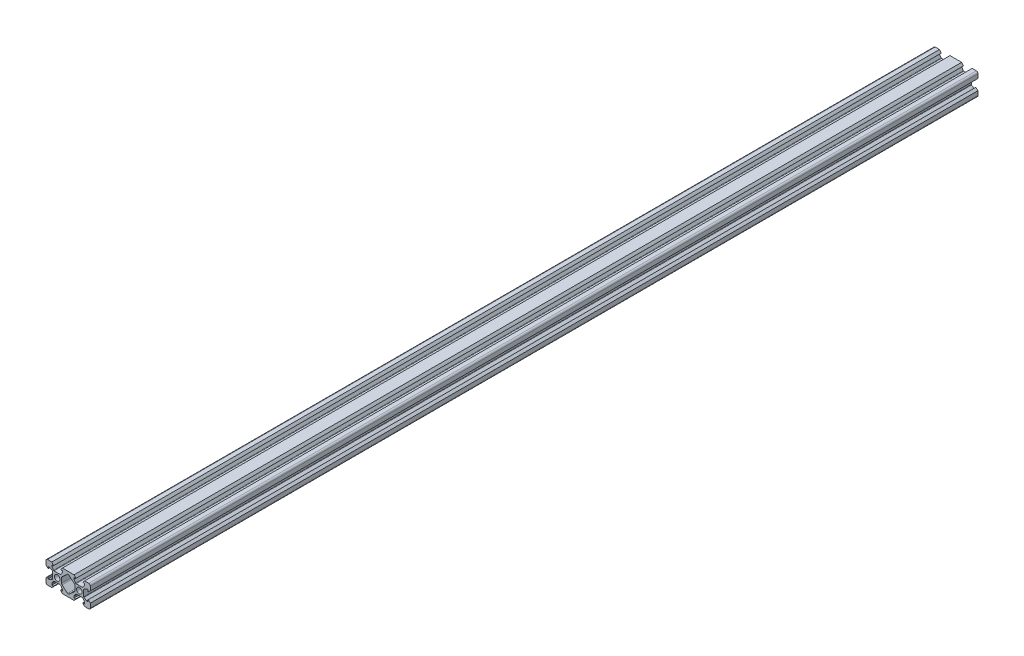
SolidWorks part; units mm, degrees
ref_plane "Спереди" through (0, 0, 0) normal (0, 0, 1) x (1, 0, 0)
ref_plane "Сверху" through (0, 0, 0) normal (0, 1, 0) x (1, 0, 0)
ref_plane "Справа" through (0, 0, 0) normal (1, 0, 0) x (0, 0, -1)
sketch "Эскиз1" plane through (0, 0, 0) normal (0, 0, 1) x (1, 0, 0)
  line L0 (-10, 17.7205) -> (-10, -8.2094) construction
  line L1 (-18.5, 14.0769) -> (-14.75, 14.0769)
  line L2 (-20, 12.5769) -> (-20, 8.8269)
  line L3 (-18.5, -5.9231) -> (-14.75, -5.9231)
  line L4 (20, 12.5769) -> (20, 8.8269)
  line L5 (10, 18.3173) -> (10, -8.2094) construction
  line L6 (0, 14.0769) -> (0, -5.9231) construction
  line L7 (-20, 4.0769) -> (20, 4.0769) construction
  line L8 (-10, 4.0769) -> (-10, 6.5769)
  line L9 (-20, -0.6731) -> (-20, -4.4231)
  line L10 (-18, 7.1769) -> (-18, 8.7269)
  line L11 (-14, 6.9078) -> (-14, 1.246)
  line L12 (-20, 8.8269) -> (-18, 7.1769)
  line L13 (-20, -0.6731) -> (-18, 0.9769)
  line L14 (-18, 0.9769) -> (-18, -0.5731)
  line L15 (-17.9, 8.8269) -> (-16.6501, 8.8269)
  line L16 (-16.3747, 8.7442) -> (-14.2246, 7.3251)
  line L17 (-16.3747, -0.5904) -> (-14.2246, 0.8287)
  line L18 (-17.9, -0.6731) -> (-16.6501, -0.6731)
  line L19 (20, 8.8269) -> (18, 7.1769)
  line L20 (20, -0.6731) -> (18, 0.9769)
  line L21 (17.9, -0.6731) -> (16.6501, -0.6731)
  line L22 (16.3747, -0.5904) -> (14.2246, 0.8287)
  line L23 (17.9, 8.8269) -> (16.6501, 8.8269)
  line L24 (18, 0.9769) -> (18, -0.5731)
  line L25 (14, 6.9078) -> (14, 1.246)
  line L26 (18, 7.1769) -> (18, 8.7269)
  line L27 (16.3747, 8.7442) -> (14.2246, 7.3251)
  line L28 (20, -0.6731) -> (20, -4.4231)
  line L29 (-14.75, 14.0769) -> (-13.1, 12.0769)
  line L30 (-13.1, 12.0769) -> (-14.65, 12.0769)
  line L31 (-14.75, 11.9769) -> (-14.75, 10.727)
  line L32 (-14.6673, 10.4516) -> (-13.2482, 8.3015)
  line L33 (-7.1691, 8.0769) -> (-12.8309, 8.0769)
  line L34 (-5.3327, 10.4516) -> (-6.7518, 8.3015)
  line L35 (-5.25, 11.9769) -> (-5.25, 10.727)
  line L36 (-6.9, 12.0769) -> (-5.35, 12.0769)
  line L37 (-5.25, 14.0769) -> (-6.9, 12.0769)
  line L38 (0, 8.8269) -> (-2, 7.1769) [skipped]
  line L39 (-2, 7.1769) -> (-2, 8.7269) [skipped]
  line L40 (-2.1, 8.8269) -> (-3.3499, 8.8269) [skipped]
  line L41 (-3.6253, 8.7442) -> (-5.7754, 7.3251) [skipped]
  line L42 (-6, 1.246) -> (-6, 6.9078) [skipped]
  line L43 (-3.6253, -0.5904) -> (-5.7754, 0.8287) [skipped]
  line L44 (-2.1, -0.6731) -> (-3.3499, -0.6731) [skipped]
  line L45 (-2, 0.9769) -> (-2, -0.5731) [skipped]
  line L46 (0, -0.6731) -> (-2, 0.9769) [skipped]
  line L47 (-5.25, -5.9231) -> (-6.9, -3.9231)
  line L48 (-6.9, -3.9231) -> (-5.35, -3.9231)
  line L49 (-5.25, -3.8231) -> (-5.25, -2.5733)
  line L50 (-5.3327, -2.2978) -> (-6.7518, -0.1477)
  line L51 (-12.8309, 0.0769) -> (-7.1691, 0.0769)
  line L52 (-14.6673, -2.2978) -> (-13.2482, -0.1477)
  line L53 (-14.75, -3.8231) -> (-14.75, -2.5733)
  line L54 (-13.1, -3.9231) -> (-14.65, -3.9231)
  line L55 (-14.75, -5.9231) -> (-13.1, -3.9231)
  line L56 (14.75, -5.9231) -> (13.1, -3.9231)
  line L57 (13.1, -3.9231) -> (14.65, -3.9231)
  line L58 (14.75, -3.8231) -> (14.75, -2.5733)
  line L59 (14.6673, -2.2978) -> (13.2482, -0.1477)
  line L60 (12.8309, 0.0769) -> (7.1691, 0.0769)
  line L61 (5.3327, -2.2978) -> (6.7518, -0.1477)
  line L62 (5.25, -3.8231) -> (5.25, -2.5733)
  line L63 (6.9, -3.9231) -> (5.35, -3.9231)
  line L64 (5.25, -5.9231) -> (6.9, -3.9231)
  line L65 (0, -0.6731) -> (2, 0.9769) [skipped]
  line L66 (2, 0.9769) -> (2, -0.5731) [skipped]
  line L67 (2.1, -0.6731) -> (3.3499, -0.6731) [skipped]
  line L68 (3.6253, -0.5904) -> (5.7754, 0.8287) [skipped]
  line L69 (6, 1.246) -> (6, 6.9078) [skipped]
  line L70 (3.6253, 8.7442) -> (5.7754, 7.3251) [skipped]
  line L71 (2.1, 8.8269) -> (3.3499, 8.8269) [skipped]
  line L72 (2, 7.1769) -> (2, 8.7269) [skipped]
  line L73 (0, 8.8269) -> (2, 7.1769) [skipped]
  line L74 (5.25, 14.0769) -> (6.9, 12.0769)
  line L75 (6.9, 12.0769) -> (5.35, 12.0769)
  line L76 (5.25, 11.9769) -> (5.25, 10.727)
  line L77 (5.3327, 10.4516) -> (6.7518, 8.3015)
  line L78 (7.1691, 8.0769) -> (12.8309, 8.0769)
  line L79 (14.6673, 10.4516) -> (13.2482, 8.3015)
  line L80 (14.75, 11.9769) -> (14.75, 10.727)
  line L81 (13.1, 12.0769) -> (14.65, 12.0769)
  line L82 (14.75, 14.0769) -> (13.1, 12.0769)
  line L83 (-5.25, 14.0769) -> (5.25, 14.0769)
  line L84 (-5.25, -5.9231) -> (5.25, -5.9231)
  line L85 (14.75, -5.9231) -> (18.5, -5.9231)
  line L86 (14.75, 14.0769) -> (18.5, 14.0769)
  line L87 (-6, 6.2202) -> (-6, 1.9336)
  line L88 (5.479, 0.7971) -> (0.6527, -3.3608)
  line L89 (-5.479, 7.3566) -> (-0.6527, 11.5146)
  line L90 (6, 6.2202) -> (6, 1.9336)
  line L91 (5.35, -3.9231) -> (5.3283, -4.1264)
  line L92 (-5.479, 0.7971) -> (-0.6527, -3.3608)
  line L93 (5.479, 7.3566) -> (0.6527, 11.5146)
  arc A0 (20, 12.5769) -> (18.5, 14.0769) centre (18.5, 12.5769) ccw
  arc A1 (-18.5, 14.0769) -> (-20, 12.5769) centre (-18.5, 12.5769) ccw
  arc A2 (18.5, -5.9231) -> (20, -4.4231) centre (18.5, -4.4231) ccw
  arc A3 (-18.5, -5.9231) -> (-20, -4.4231) centre (-18.5, -4.4231) cw
  circle A4 centre (-10, 4.0769) radius 2.5
  circle A5 centre (10, 4.0769) radius 2.5
  arc A6 (-14, 1.246) -> (-14.2246, 0.8287) centre (-14.5, 1.246) cw
  arc A7 (-14.2246, 7.3251) -> (-14, 6.9078) centre (-14.5, 6.9078) cw
  arc A8 (-16.3747, 8.7442) -> (-16.6501, 8.8269) centre (-16.6501, 8.3269) ccw
  arc A9 (-16.3747, -0.5904) -> (-16.6501, -0.6731) centre (-16.6501, -0.1731) cw
  arc A10 (-17.9, 8.8269) -> (-18, 8.7269) centre (-17.9, 8.7269) ccw
  arc A11 (-18, -0.5731) -> (-17.9, -0.6731) centre (-17.9, -0.5731) ccw
  arc A12 (18, -0.5731) -> (17.9, -0.6731) centre (17.9, -0.5731) cw
  arc A13 (17.9, 8.8269) -> (18, 8.7269) centre (17.9, 8.7269) cw
  arc A14 (16.3747, -0.5904) -> (16.6501, -0.6731) centre (16.6501, -0.1731) ccw
  arc A15 (16.3747, 8.7442) -> (16.6501, 8.8269) centre (16.6501, 8.3269) cw
  arc A16 (14.2246, 7.3251) -> (14, 6.9078) centre (14.5, 6.9078) ccw
  arc A17 (14, 1.246) -> (14.2246, 0.8287) centre (14.5, 1.246) ccw
  arc A18 (-14.65, 12.0769) -> (-14.75, 11.9769) centre (-14.65, 11.9769) ccw
  arc A19 (-14.6673, 10.4516) -> (-14.75, 10.727) centre (-14.25, 10.727) cw
  arc A20 (-12.8309, 8.0769) -> (-13.2482, 8.3015) centre (-12.8309, 8.5769) cw
  arc A21 (-6.7518, 8.3015) -> (-7.1691, 8.0769) centre (-7.1691, 8.5769) cw
  arc A22 (-5.3327, 10.4516) -> (-5.25, 10.727) centre (-5.75, 10.727) ccw
  arc A23 (-5.25, 11.9769) -> (-5.35, 12.0769) centre (-5.35, 11.9769) ccw
  arc A24 (-2, 8.7269) -> (-2.1, 8.8269) centre (-2.1, 8.7269) ccw [skipped]
  arc A25 (-3.6253, 8.7442) -> (-3.3499, 8.8269) centre (-3.3499, 8.3269) cw [skipped]
  arc A26 (-6, 6.9078) -> (-5.7754, 7.3251) centre (-5.5, 6.9078) cw [skipped]
  arc A27 (-5.7754, 0.8287) -> (-6, 1.246) centre (-5.5, 1.246) cw [skipped]
  arc A28 (-3.6253, -0.5904) -> (-3.3499, -0.6731) centre (-3.3499, -0.1731) ccw [skipped]
  arc A29 (-2.1, -0.6731) -> (-2, -0.5731) centre (-2.1, -0.5731) ccw [skipped]
  arc A30 (-5.35, -3.9231) -> (-5.25, -3.8231) centre (-5.35, -3.8231) ccw
  arc A31 (-5.3327, -2.2978) -> (-5.25, -2.5733) centre (-5.75, -2.5733) cw
  arc A32 (-7.1691, 0.0769) -> (-6.7518, -0.1477) centre (-7.1691, -0.4231) cw
  arc A33 (-13.2482, -0.1477) -> (-12.8309, 0.0769) centre (-12.8309, -0.4231) cw
  arc A34 (-14.6673, -2.2978) -> (-14.75, -2.5733) centre (-14.25, -2.5733) ccw
  arc A35 (-14.75, -3.8231) -> (-14.65, -3.9231) centre (-14.65, -3.8231) ccw
  arc A36 (14.75, -3.8231) -> (14.65, -3.9231) centre (14.65, -3.8231) cw
  arc A37 (14.6673, -2.2978) -> (14.75, -2.5733) centre (14.25, -2.5733) cw
  arc A38 (13.2482, -0.1477) -> (12.8309, 0.0769) centre (12.8309, -0.4231) ccw
  arc A39 (7.1691, 0.0769) -> (6.7518, -0.1477) centre (7.1691, -0.4231) ccw
  arc A40 (5.3327, -2.2978) -> (5.25, -2.5733) centre (5.75, -2.5733) ccw
  arc A41 (5.35, -3.9231) -> (5.25, -3.8231) centre (5.35, -3.8231) cw
  arc A42 (2.1, -0.6731) -> (2, -0.5731) centre (2.1, -0.5731) cw [skipped]
  arc A43 (3.6253, -0.5904) -> (3.3499, -0.6731) centre (3.3499, -0.1731) cw [skipped]
  arc A44 (5.7754, 0.8287) -> (6, 1.246) centre (5.5, 1.246) ccw [skipped]
  arc A45 (6, 6.9078) -> (5.7754, 7.3251) centre (5.5, 6.9078) ccw [skipped]
  arc A46 (3.6253, 8.7442) -> (3.3499, 8.8269) centre (3.3499, 8.3269) ccw [skipped]
  arc A47 (2, 8.7269) -> (2.1, 8.8269) centre (2.1, 8.7269) cw [skipped]
  arc A48 (5.25, 11.9769) -> (5.35, 12.0769) centre (5.35, 11.9769) cw
  arc A49 (5.3327, 10.4516) -> (5.25, 10.727) centre (5.75, 10.727) cw
  arc A50 (6.7518, 8.3015) -> (7.1691, 8.0769) centre (7.1691, 8.5769) ccw
  arc A51 (12.8309, 8.0769) -> (13.2482, 8.3015) centre (12.8309, 8.5769) ccw
  arc A52 (14.6673, 10.4516) -> (14.75, 10.727) centre (14.25, 10.727) ccw
  arc A53 (14.65, 12.0769) -> (14.75, 11.9769) centre (14.65, 11.9769) cw
  arc A54 (-6, 1.9336) -> (-5.479, 0.7971) centre (-4.5, 1.9336) ccw
  arc A55 (-6, 6.2202) -> (-5.479, 7.3566) centre (-4.5, 6.2202) cw
  arc A56 (6, 1.9336) -> (5.479, 0.7971) centre (4.5, 1.9336) cw
  arc A57 (6, 6.2202) -> (5.479, 7.3566) centre (4.5, 6.2202) ccw
  arc A58 (0.6527, -3.3608) -> (-0.6527, -3.3608) centre (0, -2.6032) cw
  arc A59 (0.6527, 11.5146) -> (-0.6527, 11.5146) centre (0, 10.7569) ccw
  point P0 (0, 0)
  point P8 (20, 14.0769)
  point P11 (-20, 14.0769)
  point P14 (20, -5.9231)
  point P42 (-14, 0.9769)
  point P45 (-14, 7.1769)
  point P48 (-16.5, 8.8269)
  point P51 (-16.5, -0.6731)
  point P54 (-18, 8.8269)
  point P57 (-18, -0.6731)
  point P80 (18, -0.6731)
  point P81 (18, 8.8269)
  point P82 (16.5, -0.6731)
  point P83 (16.5, 8.8269)
  point P84 (14, 7.1769)
  point P85 (14, 0.9769)
  point P155 (-10, 4.0769)
  point P178 (13.1, 0.0769)
  point P201 (6, 0.9769)
  point P224 (6.9, 8.0769)
  point P225 (10, 4.0769)
  point P230 (-6, 1.246)
  point P233 (-6, 6.9078)
  point P242 (0, -3.9231)
  point P245 (0, 12.0769)
  dimension "D3" = 1.5
  dimension "D4" = 1.5
  dimension "D6" = 5
  dimension "D8" = 0.5
  dimension "D9" = 0.5
  dimension "D10" = 0.1
  dimension "D13" = 1.5
  dimension "D14" = 1
  dimension "D1" = 40
  dimension "D2" = 20
  dimension "D5" = 2
  dimension "D7" = 6
  dimension "D11" = 4
  dimension "D12" = 4
sketch "Эскиз2" plane through (0, 0, 0) normal (0, 0, 1) x (1, 0, 0)
sketch "Эскиз3" plane through (0, 0, 0) normal (0, 0, 1) x (1, 0, 0)
extrude "Бобышка-Вытянуть1" add sketch "Эскиз1" against normal blind 800 contours L81 A53 L80 A52 L79 A51 L78 A50 L77 A49 L76 A48 L75 L74 L83 L37 L36 A23 L35 A22 L34 A21 L33 A20 L32 A19 L31 A18 L30 L29 L1 A1 L2 L12 L10 A10 L15 A8 L16 A7 L11 A6 L17 A9 L18 A11 L14 L13 L9 A3 L3
sketch "Эскиз4" plane through (0, 0, 0) normal (0, 0, 1) x (1, 0, 0)
  line L0 (-5.25, 14.0769) -> (-14.75, 14.0769)
  line L1 (-14.75, 14.0769) -> (-20.0025, 14.0769)
  line L2 (-20.0025, 14.0769) -> (-20, 11.6194)
  line L3 (-20, 12.5769) -> (-20, 8.8269) construction
